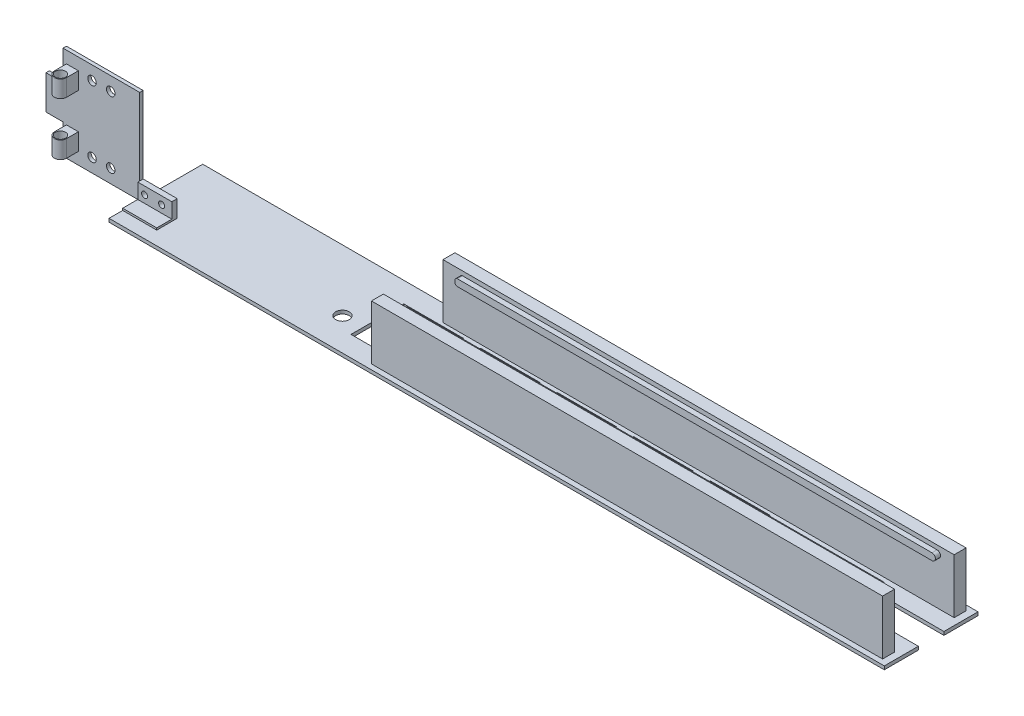
SolidWorks part; units mm, degrees
material "AISI 1045 Acero estirado en frío"
ref_plane "Front" through (0, 0, 0) normal (0, 0, 1) x (1, 0, 0)
ref_plane "Top" through (0, 0, 0) normal (0, 1, 0) x (1, 0, 0)
ref_plane "Right" through (0, 0, 0) normal (1, 0, 0) x (0, 0, -1)
sketch "Croquis1" plane through (0, 0, 0) normal (0, 0, 1) x (1, 0, 0)
  line L0 (0, 0) -> (33.6616, 0) construction
  line L1 (-22.5, -27.5) -> (22.5, -27.5)
  line L2 (-22.5, -27.5) -> (-22.5, 27.5)
  line L3 (-22.5, 27.5) -> (22.5, 27.5)
  line L4 (22.5, -27.5) -> (22.5, 27.5)
  line L5 (-22.5, -27.5) -> (22.5, 27.5) construction
  line L6 (-22.5, 27.5) -> (22.5, -27.5) construction
  line L7 (0, 0) -> (0, -8.927) construction
  circle A0 centre (5.5, 19.5) radius 2.5
  circle A1 centre (-5.5, 19.5) radius 2.5
  circle A2 centre (-5.5, -19.5) radius 2.5
  circle A3 centre (5.5, -19.5) radius 2.5
  point P0 (0, 0)
  dimension "D3" = 5
  dimension "D4" = 39
  dimension "D5" = 11
  dimension "D1" = 55
  dimension "D2" = 45
extrude "Saliente-Extruir1" add sketch "Croquis1" along normal blind 2
sketch "Croquis2" plane through (0, 0, 0) normal (0, 0, -1) x (-1, 0, 0)
  line L0 (22.5, 27.5) -> (22.5, -27.5) construction
  line L1 (22.5, 10) -> (32.5, 10)
  line L2 (22.5, 10) -> (22.5, -10)
  line L3 (22.5, -10) -> (32.5, -10)
  line L4 (32.5, 10) -> (32.5, -10)
  line L5 (0, 0) -> (49.2254, 0) construction
  dimension "D1" = 10
  dimension "D2" = 20
extrude "Saliente-Extruir2" add sketch "Croquis2" against normal blind 2
ref_plane "Plano1" through (0, 0, 0) normal (0, -1, 0) x (-1, 0, 0)
ref_plane "Plano2" through (0, -20.5, 0) normal (0, -1, 0) x (-1, 0, 0)
fillet "Redondeo1" [suppressed] radius 5
sketch "Croquis4" plane through (0, -20.5, 0) normal (0, -1, 0) x (-1, 0, 0)
  line L0 (22.5, -2) -> (-22.5, -2) construction
  line L1 (13.5, -2) -> (20.5, -2)
  line L2 (13.5, -2) -> (13.5, -9)
  line L4 (20.5, -2) -> (20.5, -9)
  line L5 (22.5, -2) -> (22.5, 0) construction
  arc A0 (13.5, -9) -> (20.5, -9) centre (17, -9) ccw
  circle A1 centre (17, -9) radius 3
  dimension "D2" = 7
  dimension "D4" = 6
  dimension "D1" = 2
  dimension "D3" = 7
  dimension "10" = 7
extrude "Saliente-Extruir4" add sketch "Croquis4" against normal blind 10
ref_plane "Plano3" through (0, 0, 0) normal (0, 1, 0) x (1, 0, 0)
mirror "Simetría1" about plane through (0, 0, 0) normal (0, 1, 0) of "Saliente-Extruir4"
sketch "Croquis6" plane through (22.5, 0, 0) normal (1, 0, 0) x (0, 0, -1)
  line L0 (-2, -27.5) -> (-2, 27.5) construction
  line L1 (0, -27.5) -> (-2, -27.5)
  line L2 (0, -27.5) -> (0, -17.5)
  line L3 (0, -17.5) -> (-2, -17.5)
  line L4 (-2, -27.5) -> (-2, -17.5)
  dimension "D1" = 10
extrude "Saliente-Extruir6" add sketch "Croquis6" along normal blind 20
sketch "Croquis7" plane through (0, -27.5, 0) normal (0, 1, 0) x (1, 0, 0)
  line L0 (42.5, -2) -> (22.5, -2) construction
  line L1 (22.5, -2) -> (22.5, 0) construction
  line L2 (42.5, 0) -> (22.5, 0) construction
  line L3 (22.5, 35) -> (477.5, 35)
  line L4 (22.5, 35) -> (22.5, -20)
  line L5 (22.5, -20) -> (477.5, -20)
  line L6 (477.5, 35) -> (477.5, -20)
  dimension "D1" = 455
  dimension "D2" = 18
  dimension "D3" = 35
extrude "Saliente-Extruir7" add sketch "Croquis7" against normal blind 2
sketch "Croquis8" plane through (0, -29.5, 0) normal (0, -1, 0) x (-1, 0, 0)
  line L5 (-477.5, 7.5) -> (81.2436, 7.5) construction
  line L6 (-477.5, -20) -> (-477.5, 35) construction
  line L7 (-477.5, -20) -> (-477.5, 35) construction
  line L12 (-477.5, 15) -> (-417.5, 15)
  line L13 (-477.5, 15) -> (-477.5, 0)
  line L14 (-477.5, 0) -> (-417.5, 0)
  line L15 (-417.5, 15) -> (-417.5, 0)
  dimension "D1" = 7.5
  dimension "D2" = 60
  dimension "D3" = 7.5
extrude "Cortar-Extruir1" cut sketch "Croquis8" against normal blind 2
sketch "Croquis9" plane through (42.5, 0, 0) normal (1, 0, 0) x (0, 0, -1)
  line L0 (-2, -17.5) -> (-2, -27.5) construction
  line L1 (-2, -17.5) -> (-3.1422, -17.5)
  line L2 (-2, -17.5) -> (-2, -27.5)
  line L4 (-3.1422, -17.5) -> (-3.1422, -26.3578)
  line L5 (-20, -27.5) -> (0, -27.5) construction
  line L6 (0, -17.5) -> (-2, -17.5) construction
  line L9 (-12, -27.5) -> (-2, -27.5)
  line L10 (-12, -27.5) -> (-12, -26.3578)
  line L11 (-12, -26.3578) -> (-3.1422, -26.3578)
  line L12 (-2, -27.5) -> (-2, -26.3578)
  dimension "D1" = 10
extrude "Saliente-Extruir8" add sketch "Croquis9" against normal up to surface (20 mm away) up to face at (22.5, 5, 1)
sketch "Croquis10" plane through (0, 0, 0) normal (0, 0, -1) x (-1, 0, 0)
  line L0 (-42.5, -27.5) -> (-42.5, -17.5) construction
  line L1 (-42.5, -17.5) -> (-22.5, -17.5) construction
  circle A0 centre (-26.5, -22) radius 1.75
  circle A1 centre (-36.5, -22) radius 1.75
  dimension "D1" = 3.5
  dimension "D3" = 6
  dimension "D4" = 4.5
  dimension "D2" = 10
extrude "Cortar-Extruir2" cut sketch "Croquis10" against normal through all
sketch "Croquis11" plane through (0, -27.5, 0) normal (0, 1, 0) x (1, 0, 0)
  line L1 (473.5, 32) -> (173.5, 32)
  line L2 (473.5, 32) -> (473.5, 25)
  line L3 (473.5, 25) -> (173.5, 25)
  line L4 (173.5, 32) -> (173.5, 25)
  line L6 (473.5, -17) -> (173.5, -17)
  line L7 (473.5, -17) -> (473.5, -10)
  line L8 (473.5, -10) -> (173.5, -10)
  line L9 (173.5, -17) -> (173.5, -10)
  line L10 (477.5, 35) -> (22.5, 35) construction
  line L11 (22.5, -20) -> (477.5, -20) construction
  line L14 (477.5, 15) -> (477.5, 35) construction
  dimension "D1" = 7
  dimension "D2" = 3
  dimension "D3" = 3
  dimension "D4" = 300
  dimension "D5" = 4
extrude "Saliente-Extruir9" add sketch "Croquis11" along normal blind 32
sketch "Croquis13" plane through (0, 0, 10) normal (0, 0, -1) x (-1, 0, 0)
  line L0 (-173.5, 4.5) -> (-173.5, -27.5) construction
  line L1 (-473.5, 4.5) -> (-473.5, -27.5) construction
  line L3 (-473.5, 4.5) -> (-173.5, 4.5) construction
  line L4 (-463.5, 2) -> (-185, 2)
  line L6 (-463.5, -2) -> (-185, -2)
  line L7 (-183.5, 0.5) -> (-183.5, -0.5)
  arc A0 (-463.5, 2) -> (-463.5, -2) centre (-463.5, 0) ccw
  arc A1 (-185, -2) -> (-183.5, -0.5) centre (-185, -0.5) ccw
  arc A2 (-185, 2) -> (-183.5, 0.5) centre (-185, 0.5) cw
  point P14 (-183.5, 2)
  dimension "D1" = 4
  dimension "D3" = 11.5
  dimension "D5" = 1.5
  dimension "D6" = 2
  dimension "D2" = 2.5
  dimension "D4" = 10
extrude "Saliente-Extruir10" add sketch "Croquis13" along normal blind 3
ref_plane "Plano4" through (0, 0, -7.5) normal (0, 0, -1) x (-1, 0, 0)
mirror "Simetría2" about plane through (0, 0, -7.5) normal (0, 0, -1) of "Saliente-Extruir10"
sketch "Croquis15" plane through (0, -29.5, 0) normal (0, -1, 0) x (1, 0, 0)
  line L0 (473.5, 13.5) -> (173.5, 13.5) construction
  line L1 (22.5, -7.5) -> (114.6531, -7.5) construction
  line L2 (22.5, -35) -> (22.5, 20) construction
  line L4 (473.5, 10) -> (473.5, 17)
  line L5 (173.5, 10) -> (473.5, 10)
  line L6 (173.5, 17) -> (173.5, 10)
  line L7 (473.5, 17) -> (173.5, 17)
  line L8 (473.5, 10) -> (473.5, 17) construction
  line L9 (173.5, 10) -> (473.5, 10) construction
  line L10 (173.5, 17) -> (173.5, 10) construction
  line L11 (473.5, 17) -> (173.5, 17) construction
  line L12 (473.5, -32) -> (473.5, -25)
  line L13 (173.5, -32) -> (473.5, -32)
  line L14 (173.5, -25) -> (173.5, -32)
  line L15 (473.5, -25) -> (173.5, -25)
  line L16 (473.5, -32) -> (473.5, -25) construction
  line L17 (173.5, -32) -> (473.5, -32) construction
  line L18 (173.5, -25) -> (173.5, -32) construction
  line L19 (473.5, -25) -> (173.5, -25) construction
  circle A0 centre (183.5, 13.5) radius 1.75
  circle A1 centre (205.5, 13.5) radius 1.75
  circle A2 centre (227.5, 13.5) radius 1.75
  circle A3 centre (249.5, 13.5) radius 1.75
  circle A4 centre (249.5, -28.5) radius 1.75
  circle A5 centre (227.5, -28.5) radius 1.75
  circle A6 centre (205.5, -28.5) radius 1.75
  circle A7 centre (183.5, -28.5) radius 1.75
  dimension "D3" = 3.5
  dimension "D4" = 10
  dimension "D1" = 0
  dimension "D2" = 0
  dimension "D5" = 4
extrude "Cortar-Extruir3" [suppressed] cut sketch "Croquis15" against normal blind 3
chamfer "Chaflán1" [suppressed] distance 5 angle 25
fillet "Redondeo3" [suppressed] radius 5
chamfer "Chaflán2" [suppressed] distance 3 angle 25
chamfer "Chaflán3" [suppressed] distance 3 angle 25
sketch "Croquis17" plane through (0, -27.5, 0) normal (0, 1, 0) x (1, 0, 0)
  line L0 (42.5, -12) -> (42.5, 0) construction
  line L1 (22.5, -20) -> (477.5, -20) construction
  circle A0 centre (140.5, -1) radius 4
  dimension "D2" = 19
  dimension "D3" = 8
  dimension "D1" = 98
extrude "Cortar-Extruir4" cut sketch "Croquis17" against normal blind 10
sketch "Croquis18" plane through (0, -27.5, 0) normal (0, 1, 0) x (1, 0, 0)
  line L0 (417.5, 7.5) -> (22.5, 7.5) construction
  line L1 (417.5, 0) -> (417.5, 15) construction
  line L2 (22.5, 35) -> (22.5, 0) construction
  line L3 (477.5, 35) -> (22.5, 35) construction
  line L4 (152.5, -8) -> (187.5, -8)
  line L5 (152.5, -8) -> (152.5, 23)
  line L6 (152.5, 23) -> (187.5, 23)
  line L7 (187.5, -8) -> (187.5, 23)
  line L8 (152.5, -8) -> (187.5, 23) construction
  line L9 (152.5, 23) -> (187.5, -8) construction
  line L10 (42.5, -12) -> (42.5, -3.1422) construction
  line L11 (197.5, -8) -> (197.5, 23)
  line L12 (197.5, -8) -> (232.5, -8)
  line L13 (232.5, -8) -> (232.5, 23)
  line L14 (197.5, 23) -> (232.5, 23)
  line L15 (242.5, -8) -> (242.5, 23)
  line L16 (242.5, -8) -> (277.5, -8)
  line L17 (277.5, -8) -> (277.5, 23)
  line L18 (242.5, 23) -> (277.5, 23)
  line L19 (287.5, -8) -> (287.5, 23)
  line L20 (287.5, -8) -> (322.5, -8)
  line L21 (322.5, -8) -> (322.5, 23)
  line L22 (287.5, 23) -> (322.5, 23)
  line L23 (332.5, -8) -> (332.5, 23)
  line L24 (332.5, -8) -> (367.5, -8)
  line L25 (367.5, -8) -> (367.5, 23)
  line L26 (332.5, 23) -> (367.5, 23)
  point P6 (170, 7.5)
  dimension "D1" = 12
  dimension "D2" = 110
  dimension "D3" = 35
  dimension "D4" = 5
extrude "Cortar-Extruir5" cut sketch "Croquis18" against normal blind 10
sketch "Croquis19" plane through (0, -27.5, 0) normal (0, 1, 0) x (1, 0, 0)
  line L0 (367.5, -8) -> (367.5, 23) construction
  line L1 (22.5, -20) -> (477.5, -20) construction
  circle A0 centre (384.5, 0) radius 4
  dimension "D1" = 8
  dimension "D2" = 17
  dimension "D3" = 20
extrude "Cortar-Extruir6" cut sketch "Croquis19" against normal blind 10
sketch "Croquis20" plane through (0, -27.5, 0) normal (0, 1, 0) x (1, 0, 0)
  line L0 (22.5, -20) -> (477.5, -20) construction
  circle A0 centre (154.3444, -20) radius 28.8368
extrude "Cortar-Extruir7" [suppressed] cut sketch "Croquis20" against normal blind 10
sketch "Croquis21" plane through (0, -27.5, 0) normal (0, 1, 0) x (1, 0, 0)
  line L0 (173.5, -10) -> (173.5, -17) construction
  line L1 (135.355, 8.9627) -> (178.5, 8.9627)
  line L2 (135.355, 8.9627) -> (135.355, -36.3146)
  line L3 (135.355, -36.3146) -> (178.5, -36.3146)
  line L4 (178.5, 8.9627) -> (178.5, -36.3146)
  dimension "D1" = 5
extrude "Cortar-Extruir8" [suppressed] cut sketch "Croquis21" against normal blind 10
sketch "Croquis22" plane through (0, -29.5, 0) normal (0, -1, 0) x (1, 0, 0)
  circle A0 centre (384.5, 0) radius 6.5
  circle A1 centre (384.5, 0) radius 4 construction
  circle A2 centre (384.5, 0) radius 4
  dimension "D1" = 13
extrude "Saliente-Extruir11" add sketch "Croquis22" along normal blind 8.5
equation "\"6o\"=64.9993"
